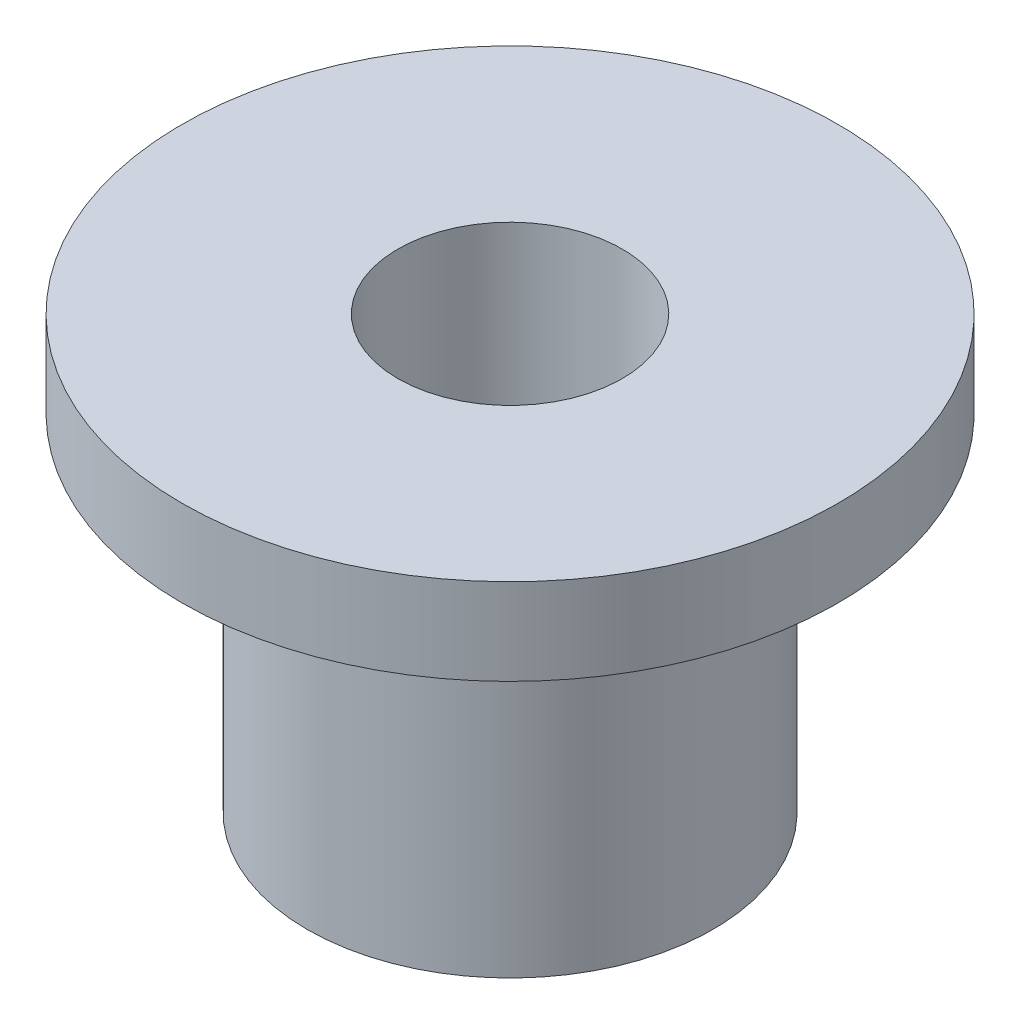
SolidWorks part; units mm, degrees
ref_plane "Front Plane" through (0, 0, 0) normal (0, 0, 1) x (1, 0, 0)
ref_plane "Top Plane" through (0, 0, 0) normal (0, 1, 0) x (1, 0, 0)
ref_plane "Right Plane" through (0, 0, 0) normal (1, 0, 0) x (0, 0, -1)
sketch "Sketch1" plane through (0, 0, 0) normal (0, 0, 1) x (1, 0, 0)
  line L0 (0, 5.1734) -> (0, -5.1734) construction
  line L8 (-2.6, 0) -> (-2.6, 10)
  line L9 (-2.6, 10) -> (-7.6, 10)
  line L10 (-7.6, 10) -> (-7.6, 8)
  line L11 (-7.6, 8) -> (-4.7, 8)
  line L12 (-4.7, 8) -> (-4.7, 0)
  line L13 (-4.7, 0) -> (-2.6, 0)
  point P4 (0, 0)
  dimension "D1" = 2.6
  dimension "D2" = 4.7
  dimension "D3" = 5
  dimension "D4" = 2
  dimension "D5" = 8
revolve "Revolve1" add sketch "Sketch1" angle 360 about L0
